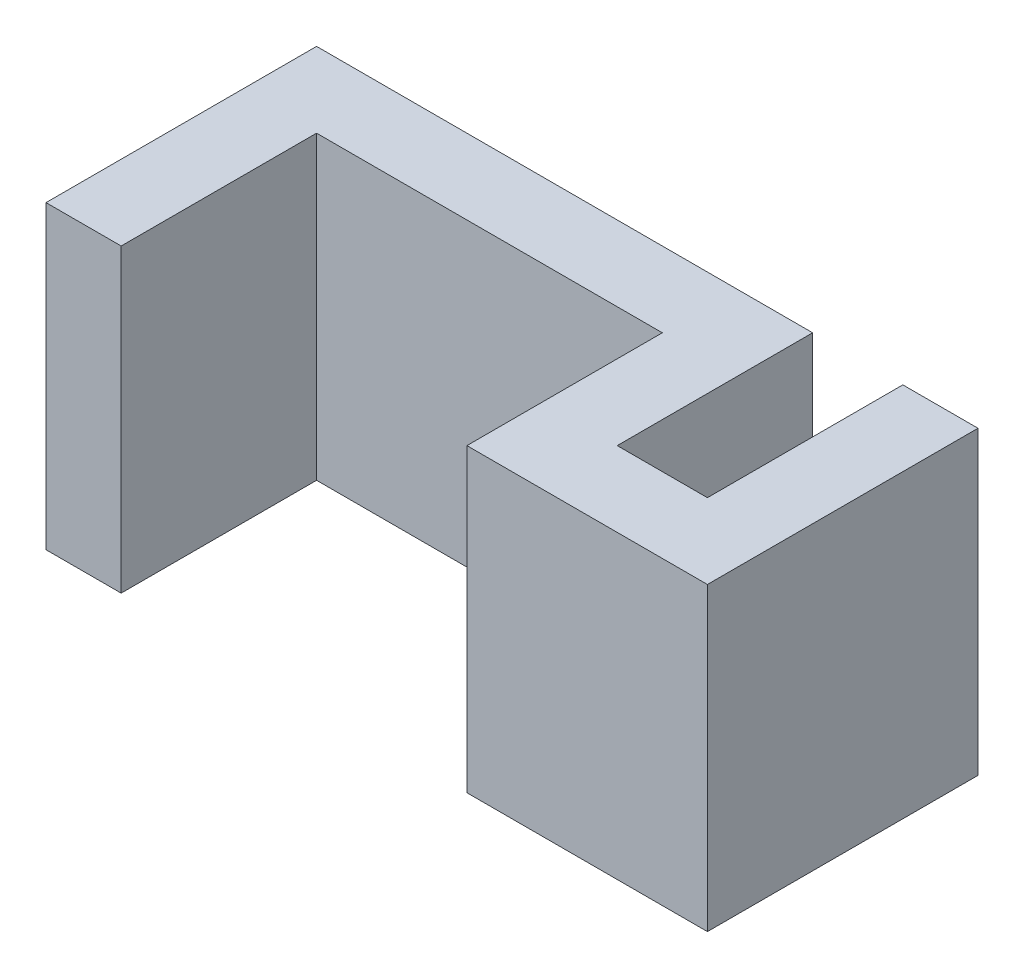
SolidWorks part; units mm, degrees
ref_plane "Front Plane" through (0, 0, 0) normal (0, 0, 1) x (1, 0, 0)
ref_plane "Top Plane" through (0, 0, 0) normal (0, 1, 0) x (1, 0, 0)
ref_plane "Right Plane" through (0, 0, 0) normal (1, 0, 0) x (0, 0, -1)
sketch "Sketch1" plane through (0, 0, 0) normal (0, 1, 0) x (1, 0, 0)
  line L0 (0, 0) -> (0, 33.02)
  line L1 (0, 33.02) -> (58.42, 33.02)
  line L2 (58.42, 33.02) -> (58.42, 0)
  line L3 (58.42, 0) -> (99.06, 0)
  line L4 (99.06, 0) -> (99.06, 45.72)
  line L5 (99.06, 45.72) -> (86.36, 45.72)
  line L6 (86.36, 45.72) -> (86.36, 12.7)
  line L7 (86.36, 12.7) -> (71.12, 12.7)
  line L8 (71.12, 12.7) -> (71.12, 45.72)
  line L9 (71.12, 45.72) -> (-12.7, 45.72)
  line L10 (-12.7, 45.72) -> (-12.7, 0)
  line L11 (-12.7, 0) -> (0, 0)
  point P12 (36.2594, 0)
  dimension "D1" = 12.7
  dimension "D2" = 33.02
  dimension "D3" = 12.7
  dimension "D4" = 15.24
  dimension "D5" = 58.42
  dimension "D6" = 12.7
  dimension "D7" = 12.7
  dimension "D8" = 12.7
extrude "Boss-Extrude1" add sketch "Sketch1" along normal blind 50.8 contours L10 L11 L0 L1 L2 L3 L4 L5 L6 L7 L8 L9
